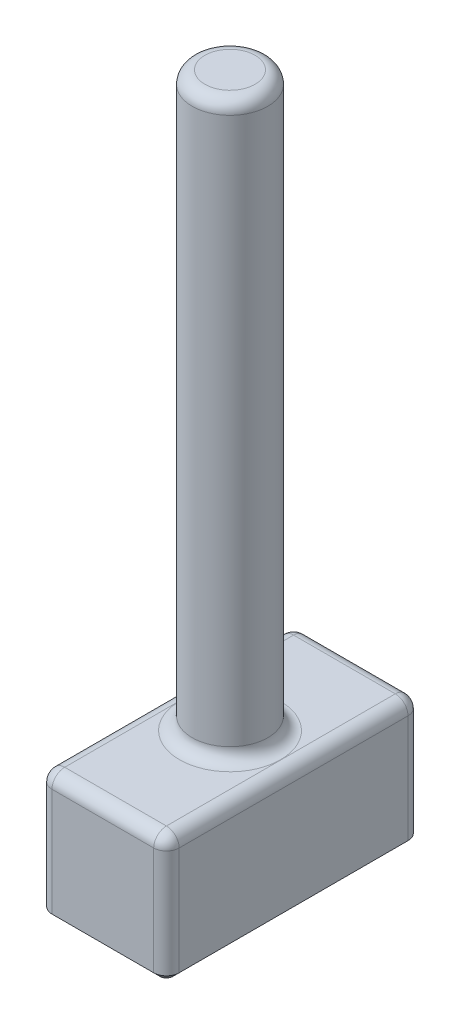
SolidWorks part; units mm, degrees
ref_plane "Front Plane" through (0, 0, 0) normal (0, 0, 1) x (1, 0, 0)
ref_plane "Top Plane" through (0, 0, 0) normal (0, 1, 0) x (1, 0, 0)
ref_plane "Right Plane" through (0, 0, 0) normal (1, 0, 0) x (0, 0, -1)
sketch "Sketch1" plane through (0, 0, 0) normal (0, 1, 0) x (1, 0, 0)
  circle A0 centre (0, 0) radius 2.975
  dimension "D1" = 5.95
extrude "Boss-Extrude1" add sketch "Sketch1" along normal blind 50
sketch "Sketch2" plane through (0, 0, 0) normal (0, 0, 1) x (1, 0, 0)
  line L4 (-5, -5) -> (5, -5)
  line L5 (-5, -5) -> (-5, 5)
  line L6 (-5, 5) -> (5, 5)
  line L7 (5, -5) -> (5, 5)
  line L8 (-5, -5) -> (5, 5) construction
  line L9 (-5, 5) -> (5, -5) construction
  point P0 (0, 0)
  dimension "D1" = 10
extrude "Boss-Extrude2" add sketch "Sketch2" along normal mid plane 20
fillet "Fillet1" radius 1 10 edges at (0, 5, -2.975) (-5, 0, 10) (-5, 0, -10) (5, 0, -10) (5, 0, 10) (0, 5, 10) (-5, 5, 0) (0, 5, -10) (5, 5, 0) (0, 50, 2.975)
chamfer "Chamfer1" distance 0.5 angle 45 8 edges at (5, -5, 0) (4.7071, -5, 9.7071) (4.7071, -5, -9.7071) (0, -5, 10) (0, -5, -10) (-4.7071, -5, 9.7071) (-4.7071, -5, -9.7071) (-5, -5, 0)
